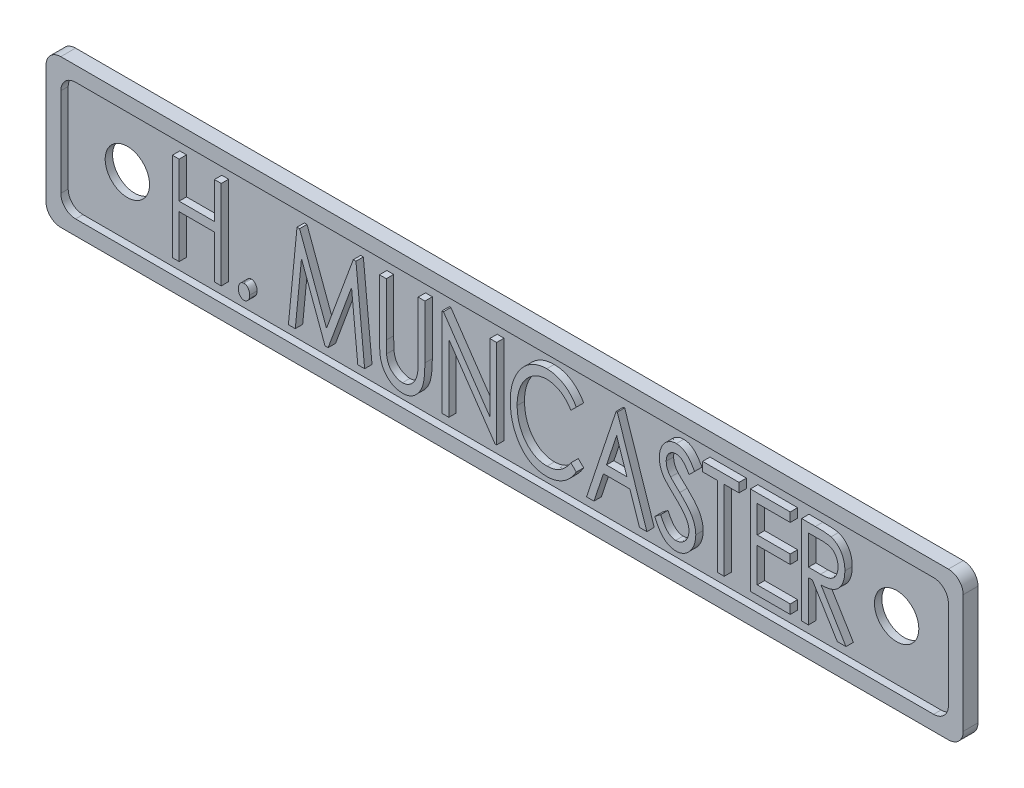
SolidWorks part; units mm, degrees
ref_plane "Front Plane" through (0, 0, 0) normal (0, 0, 1) x (1, 0, 0)
ref_plane "Top Plane" through (0, 0, 0) normal (0, 1, 0) x (1, 0, 0)
ref_plane "Right Plane" through (0, 0, 0) normal (1, 0, 0) x (0, 0, -1)
sketch "Sketch1" plane through (0, 0, 0) normal (0, 0, 1) x (1, 0, 0)
  line L1 (-31, 5) -> (31, 5)
  line L2 (-31, 5) -> (-31, -5)
  line L3 (-31, -5) -> (31, -5)
  line L4 (31, 5) -> (31, -5)
  line L5 (-31, 5) -> (31, -5) construction
  line L6 (-31, -5) -> (31, 5) construction
  point P0 (0, 0)
  dimension "D1" = 62
  dimension "D2" = 10
extrude "Boss-Extrude1" add sketch "Sketch1" along normal blind 1
sketch "Sketch2" plane through (0, 0, 1) normal (0, 0, 1) x (1, 0, 0)
  line L18 (-30, -4) -> (30, -4)
  line L19 (30, -4) -> (30, 4)
  line L20 (30, 4) -> (-30, 4)
  line L21 (-30, 4) -> (-30, -4)
  line L22 (-30, -4) -> (30, -4)
  line L23 (30, -4) -> (30, 4)
  line L24 (30, 4) -> (-30, 4)
  line L25 (-30, 4) -> (-30, -4)
  dimension "D1" = 1
extrude "Cut-Extrude2" cut sketch "Sketch2" against normal blind 0.5
fillet "Fillet1" radius 1 8 edges at (-30, 4, 0.75) (30, 4, 0.75) (-30, -4, 0.75) (30, -4, 0.75) (31, -5, 0.5) (31, 5, 0.5) (-31, -5, 0.5) (-31, 5, 0.5)
sketch "Sketch3" plane through (0, 0, 0.5) normal (0, 0, 1) x (1, 0, 0)
  line L0 (-31, 4) -> (-31, -4) construction
  line L1 (31, -4) -> (31, 4) construction
  circle A0 centre (-26, 0) radius 1.5
  circle A1 centre (26, 0) radius 1.5
  point P4 (0, 0)
  dimension "D3" = 3
  dimension "D4" = 3
  dimension "D1" = 5
  dimension "D2" = 5
extrude "Cut-Extrude3" cut sketch "Sketch3" against normal through all
sketch "Sketch4" plane through (0, 0, 0.5) normal (0, 0, 1) x (1, 0, 0)
  line L0 (-23, -3) -> (23, -3) construction
  line L1 (-31, 4) -> (-31, -4) construction
  line L2 (-29, -4) -> (29, -4) construction
  line L3 (31, -4) -> (31, 4) construction
  text T0 "H. MUNCASTER" font "Century Gothic" height 6
  dimension "D1" = 8
  dimension "D2" = 1
  dimension "D3" = 8
extrude "Boss-Extrude2" add sketch "Sketch4" along normal blind 0.5
